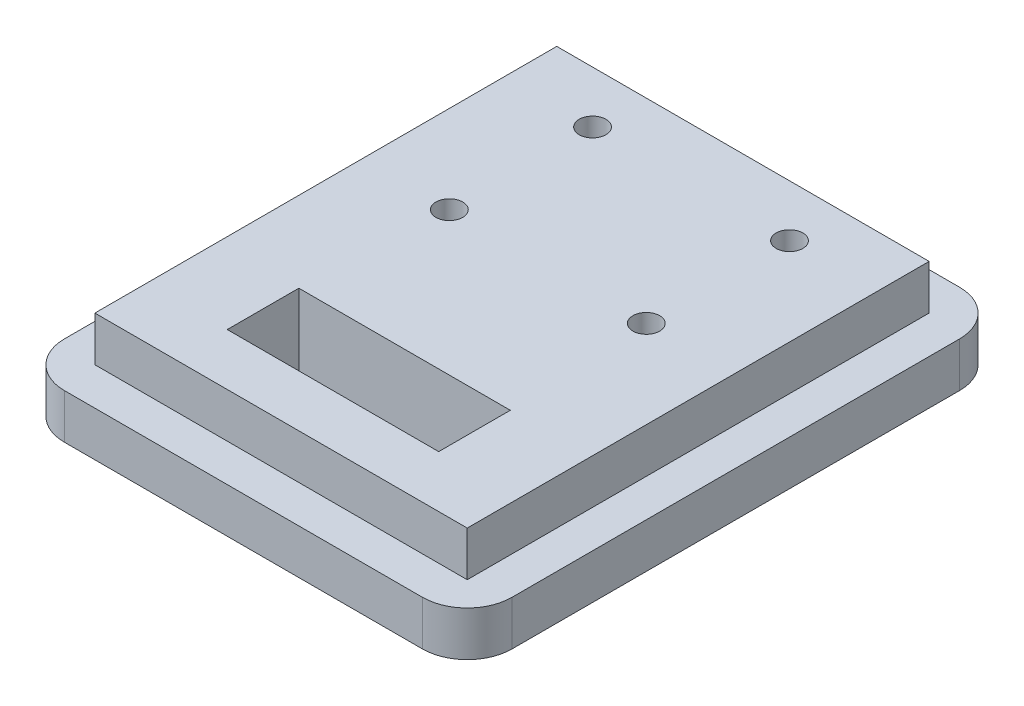
SolidWorks part; units mm, degrees
ref_plane "Front Plane" through (0, 0, 0) normal (0, 0, 1) x (1, 0, 0)
ref_plane "Top Plane" through (0, 0, 0) normal (0, 1, 0) x (1, 0, 0)
ref_plane "Right Plane" through (0, 0, 0) normal (1, 0, 0) x (0, 0, -1)
sketch "Sketch1" plane through (0, 0, 0) normal (0, 1, 0) x (1, 0, 0)
  line L1 (-15.875, -19.05) -> (15.875, -19.05)
  line L2 (-15.875, -19.05) -> (-15.875, 19.05)
  line L3 (-15.875, 19.05) -> (15.875, 19.05)
  line L4 (15.875, -19.05) -> (15.875, 19.05)
  line L5 (-15.875, -19.05) -> (15.875, 19.05) construction
  line L6 (-15.875, 19.05) -> (15.875, -19.05) construction
  point P0 (0, 0)
  dimension "D1" = 38.1
  dimension "D2" = 31.75
extrude "Boss-Extrude1" add sketch "Sketch1" along normal blind 6.35
sketch "Sketch2" plane through (0, 6.35, 0) normal (0, 1, 0) x (1, 0, 0)
  line L0 (6.985, 2.54) -> (0, 2.54) construction
  line L3 (0, 0) -> (0, 50000) construction
  line L4 (15.875, 19.05) -> (-15.875, 19.05) construction
  line L5 (-6.985, 2.54) -> (-6.985, 50002.54) construction
  line L6 (6.985, 7.62) -> (6.985, 50007.62) construction
  line L7 (-6.985, 12.7) -> (6.985, 12.7) construction
  circle A0 centre (-6.985, 2.54) radius 0.95
  circle A1 centre (6.985, 2.54) radius 0.95
  circle A2 centre (-6.985, 12.7) radius 0.95
  circle A3 centre (6.985, 12.7) radius 0.95
  point P21 (0, 12.7)
  dimension "D3" = 1.9
  dimension "D1" = 13.97
  dimension "D2" = 6.35
  dimension "D4" = 16.51
extrude "Cut-Extrude1" cut sketch "Sketch2" against normal through all
sketch "Sketch3" plane through (0, 6.35, 0) normal (0, 1, 0) x (1, 0, 0)
  line L0 (0, 0) -> (0, 50000) construction
  line L2 (-7.5, -12.7) -> (7.5, -12.7)
  line L3 (-7.5, -12.7) -> (-7.5, -7.62)
  line L4 (-7.5, -7.62) -> (7.5, -7.62)
  line L5 (7.5, -12.7) -> (7.5, -7.62)
  line L6 (-7.5, -12.7) -> (7.5, -7.62) construction
  line L7 (-7.5, -7.62) -> (7.5, -12.7) construction
  circle A0 centre (-6.985, 2.54) radius 0.95 construction
  point P3 (0, -10.16)
  dimension "D1" = 5.08
  dimension "D2" = 15
  dimension "D3" = 12.7
extrude "Cut-Extrude2" cut sketch "Sketch3" against normal through all
sketch "Sketch4" plane through (0, 6.35, 0) normal (0, 1, 0) x (1, 0, 0)
  line L0 (15.875, -19.05) -> (15.875, 19.05) construction
  line L1 (-13.208, -16.383) -> (13.208, -16.383)
  line L2 (-13.208, -16.383) -> (-13.208, 16.383)
  line L3 (-13.208, 16.383) -> (13.208, 16.383)
  line L4 (13.208, -16.383) -> (13.208, 16.383)
  line L5 (-13.208, -16.383) -> (13.208, 16.383) construction
  line L6 (-13.208, 16.383) -> (13.208, -16.383) construction
  line L7 (15.875, 19.05) -> (-15.875, 19.05) construction
  line L12 (15.875, -19.05) -> (15.875, 19.05)
  line L13 (15.875, 19.05) -> (-15.875, 19.05)
  line L14 (-15.875, 19.05) -> (-15.875, -19.05)
  line L15 (-15.875, -19.05) -> (15.875, -19.05)
  line L16 (15.875, -19.05) -> (15.875, 19.05)
  line L17 (15.875, 19.05) -> (-15.875, 19.05)
  line L18 (-15.875, 19.05) -> (-15.875, -19.05)
  line L19 (-15.875, -19.05) -> (15.875, -19.05)
  point P0 (0, 0)
  dimension "D1" = 2.667
  dimension "D2" = 2.667
  dimension "D3" = 0
extrude "Cut-Extrude3" cut sketch "Sketch4" against normal blind 3.175
fillet "Fillet1" radius 3.175 4 edges at (15.875, 1.5875, 19.05) (-15.875, 1.5875, 19.05) (15.875, 1.5875, -19.05) (-15.875, 1.5875, -19.05)
